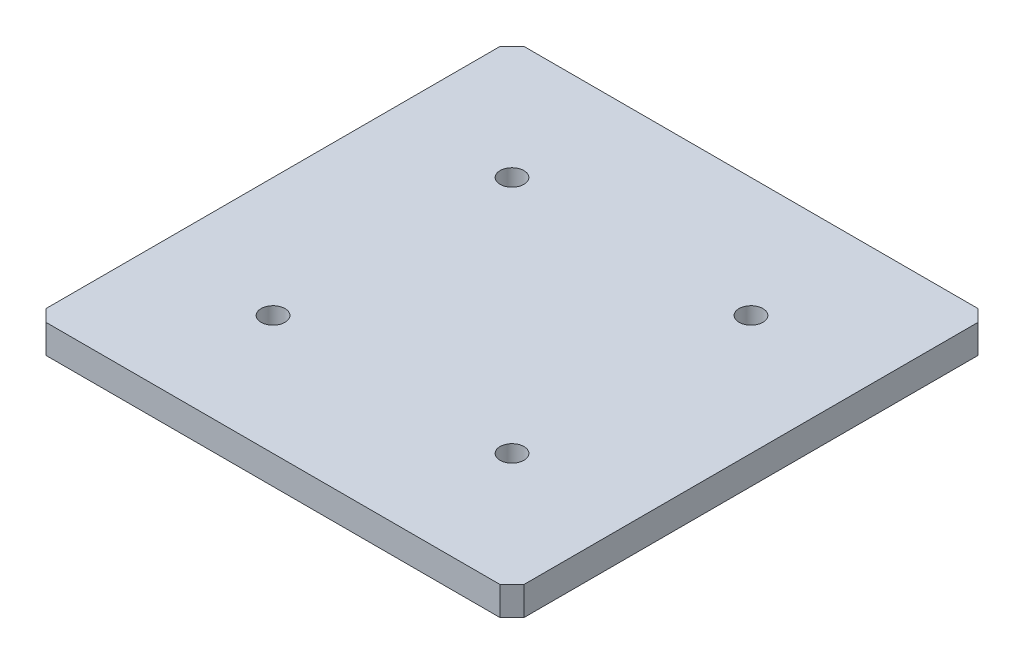
SolidWorks part; units mm, degrees
material "AU4G - 2017A"
ref_plane "Plan de face" through (0, 0, 0) normal (0, 0, 1) x (1, 0, 0)
ref_plane "Plan de dessus" through (0, 0, 0) normal (0, 1, 0) x (1, 0, 0)
ref_plane "Plan de droite" through (0, 0, 0) normal (1, 0, 0) x (0, 0, -1)
sketch "Sketch1" plane through (0, 0, 0) normal (0, 1, 0) x (1, 0, 0)
  line L0 (-100, -100) -> (100, 100) construction
  line L1 (-100, -100) -> (100, -100)
  line L2 (-100, -100) -> (-100, 100)
  line L3 (-100, 100) -> (100, 100)
  line L4 (100, -100) -> (100, 100)
  point P4 (0, 0)
  dimension "D1" = 200
  dimension "D2" = 200
extrude "Boss-Extrude1" add sketch "Sketch1" along normal blind 12
sketch "Sketch2" plane through (0, 12, 0) normal (0, 1, 0) x (1, 0, 0)
  circle A0 centre (0, 0) radius 30.5
  dimension "D1" = 61
sketch "Sketch3" plane through (0, 12, 0) normal (0, 1, 0) x (1, 0, 0)
  line L0 (-100, 0) -> (-89.4469, 0) construction
  line L1 (-100, 100) -> (-100, -100) construction
  line L2 (0, -100) -> (0, -62.1463) construction
  line L3 (-100, -100) -> (100, -100) construction
  circle A0 centre (-50, 50) radius 5
  circle A1 centre (50, 50) radius 5
  circle A2 centre (-50, -50) radius 5
  circle A3 centre (50, -50) radius 5
  dimension "D3" = 10
  dimension "D1" = 100
  dimension "D2" = 100
extrude "Cut-Extrude2" cut sketch "Sketch3" against normal up to next
chamfer "Chamfer1" distance 5 angle 45 4 edges at (-100, 6, -100) (100, 6, -100) (100, 6, 100) (-100, 6, 100)
